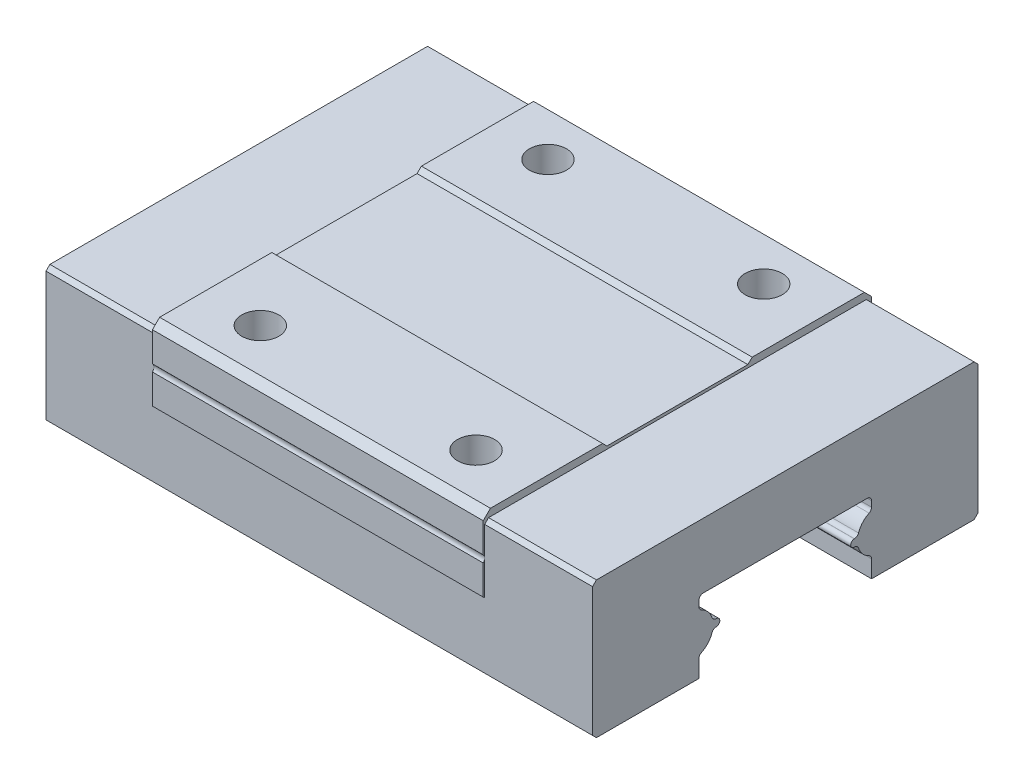
SolidWorks part; units mm, degrees
ref_plane "前视基准面" through (0, 0, 0) normal (0, 0, 1) x (1, 0, 0)
ref_plane "上视基准面" through (0, 0, 0) normal (0, 1, 0) x (1, 0, 0)
ref_plane "右视基准面" through (0, 0, 0) normal (1, 0, 0) x (0, 0, -1)
other "Configuration Table"
ref_plane "基准面1" through (-19, 0, 0) normal (-1, 0, 0) x (0, -1, 0)
sketch "草图1" plane through (-19, 0, 0) normal (-1, 0, 0) x (0, -1, 0)
  line L0 (1, 13.4) -> (-8.5, 13.4)
  line L1 (-8.5, 13.4) -> (-8.5, -13.4)
  line L2 (-8.5, -13.4) -> (1, -13.4)
  line L3 (1, -13.4) -> (1, -6)
  line L4 (1, -6) -> (-0.4089, -6)
  line L5 (-1.51, -5.04) -> (-1.51, -4.8)
  line L6 (-2.01, -4.8) -> (-2.01, -5.04)
  line L7 (-3.1111, -6) -> (-4, -6)
  line L8 (-4, -6) -> (-4, 6)
  line L9 (-4, 6) -> (-3.1111, 6)
  line L10 (-2.01, 5.04) -> (-2.01, 4.8)
  line L11 (-1.51, 4.8) -> (-1.51, 5.04)
  line L12 (-0.4089, 6) -> (1, 6)
  line L13 (1, 6) -> (1, 13.4)
  arc A0 (-0.4089, -6) -> (-1.51, -5.04) centre (-1.76, -6.4382) ccw
  arc A1 (-1.51, -4.8) -> (-2.01, -4.8) centre (-1.76, -4.8) ccw
  arc A2 (-2.01, -5.04) -> (-3.1111, -6) centre (-1.76, -6.4382) ccw
  arc A3 (-3.1111, 6) -> (-2.01, 5.04) centre (-1.76, 6.4382) ccw
  arc A4 (-2.01, 4.8) -> (-1.51, 4.8) centre (-1.76, 4.8) ccw
  arc A5 (-1.51, 5.04) -> (-0.4089, 6) centre (-1.76, 6.4382) ccw
extrude "凸台-拉伸1" add sketch "草图1" against normal blind 38
sketch "草图2" plane through (0, 0, -13.4) normal (0, 0, -1) x (-1, 0, 0)
  line L0 (11.5, 8.5) -> (11.5, 3.8)
  line L1 (11.5, 3.8) -> (-11.5, 3.8)
  line L2 (-11.5, 3.8) -> (-11.5, 8.5)
  line L3 (-11.5, 8.5) -> (11.5, 8.5)
extrude "凸台-拉伸2" add sketch "草图2" along normal blind 0.1
sketch "草图3" plane through (0, 0, 13.4) normal (0, 0, 1) x (1, 0, 0)
  line L0 (11.5, 8.5) -> (11.5, 3.9)
  line L1 (11.5, 3.9) -> (-11.5, 3.9)
  line L2 (-11.5, 3.9) -> (-11.5, 8.5)
  line L3 (-11.5, 8.5) -> (11.5, 8.5)
extrude "凸台-拉伸3" add sketch "草图3" along normal blind 0.1
sketch "草图4" plane through (0, 8.5, 0) normal (0, 1, 0) x (-1, 0, 0)
  line L0 (11.5, 13.5) -> (11.5, -13.5)
  line L1 (11.5, -13.5) -> (-11.5, -13.5)
  line L2 (-11.5, -13.5) -> (-11.5, 13.5)
  line L3 (-11.5, 13.5) -> (11.5, 13.5)
extrude "凸台-拉伸4" add sketch "草图4" along normal blind 0.5
sketch "草图5" plane through (11.5, 0, 0) normal (1, 0, 0) x (0, 0, -1)
  line L0 (-13.5, 6.4449) -> (-13.5, 5.9551)
  arc A0 (-13.5, 5.9551) -> (-13.5, 6.4449) centre (-13.75, 6.2) ccw
extrude "切除-拉伸1" cut sketch "草图5" against normal blind 23
sketch "草图6" plane through (11.5, 0, 0) normal (1, 0, 0) x (0, 0, -1)
  line L0 (4.9, 9) -> (-4.9, 9)
  line L1 (-4.9, 9) -> (-4.9, 8.7)
  line L2 (-4.9, 8.7) -> (4.9, 8.7)
  line L3 (4.9, 8.7) -> (4.9, 9)
extrude "切除-拉伸2" cut sketch "草图6" against normal through all
draft "拔模1" type of draft neutral plane draft angle 45 faces to draft 1 face at (0, 3.9, 13.45) neutral plane through (0, 0, 13.5) neutral plane normal (0, 0, 1) parameters "D1"=45
draft "拔模2" type of draft neutral plane draft angle 45 faces to draft 1 face at (0, 3.8, -13.45) neutral plane through (19, 8.5, -13.4) neutral plane normal (0, 0, -1) parameters "D1"=45
draft "拔模3" type of draft neutral plane draft angle 45 faces to draft 2 face at (0, 8.85, 4.9) face at (0, 8.85, -4.9) neutral plane through (-19, 8.7, 4.9) neutral plane normal (0, 1, 0) parameters "D1"=45
hole_wizard "M2 间隙孔1" positions "草图8" profile "草图7" hole size "M2" standard "ANSI Metric"
sketch "草图8" plane through (0, 9, 0) normal (0, 1, 0) x (1, 0, 0)
  point P0 (7.5, -10)
  point P1 (-7.5, -10)
  point P2 (-7.5, 10)
  point P3 (7.5, 10)
sketch "草图7" plane through (7.5, 9, 10) normal (1, 0, 0) x (0, 0, 1)
  line L0 (0, 0) -> (0, 4.2751)
  line L1 (0, 4.2751) -> (1.29, 3.5)
  line L2 (1.29, 3.5) -> (1.29, 0)
  line L5 (1.29, 0) -> (0, 0)
  line L10 (0, 4.2751) -> (-1.29, 3.5) construction
  line L11 (0, -6.35) -> (0, 107.95) construction
  dimension "孔直径" = 2.58
  dimension "孔深度" = 3.5
  dimension "导头角度" = 118
chamfer "倒角1" distance 0.27 angle 45 6 edges at (0, -1, -13.4) (-15.25, 8.5, -13.4) (0, -1, 13.4) (-15.25, 8.5, 13.4) (15.25, 8.5, -13.4) (15.25, 8.5, 13.4)
chamfer "倒角2" distance 0.5 angle 45 2 edges at (0, 9, 13.5) (0, 9, -13.5)
fillet "圆角1" radius 0.3 10 edges at (0, 2.01, -5.04) (0, 0.4089, 6) (0, 0.4089, -6) (0, 4, 6) (0, 3.1111, -6) (0, 3.1111, 6) (0, 1.51, -5.04) (0, 2.01, 5.04) (0, 1.51, 5.04) (0, 4, -6)
